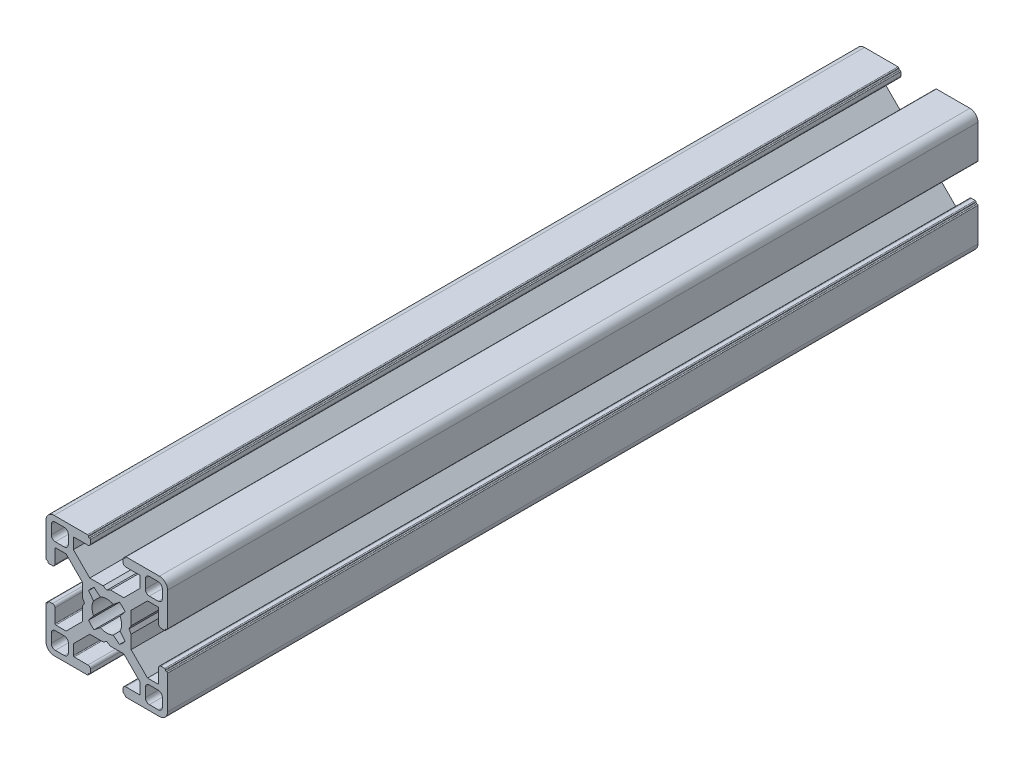
SolidWorks part; units mm, degrees
ref_plane "Płaszczyzna przednia" through (0, 0, 0) normal (0, 0, 1) x (1, 0, 0)
ref_plane "Płaszczyzna górna" through (0, 0, 0) normal (0, 1, 0) x (1, 0, 0)
ref_plane "Płaszczyzna prawa" through (0, 0, 0) normal (1, 0, 0) x (0, 0, -1)
sketch "Szkic1" plane through (0, 0, 0) normal (0, 0, 1) x (1, 0, 0)
  line L0 (109.26, 48.76) -> (107.06, 48.76)
  line L1 (106.06, 47.76) -> (106.06, 45.56)
  line L2 (107.06, 44.56) -> (109.26, 44.56)
  line L3 (110.26, 45.56) -> (110.26, 47.76)
  line L4 (94.9599, 38.3406) -> (93.4241, 39.5784)
  line L5 (92.0547, 38.2147) -> (93.2794, 36.6601)
  line L6 (93.2794, 33.4599) -> (92.0547, 31.9053)
  line L7 (93.4241, 30.5416) -> (94.9599, 31.7794)
  line L8 (98.1601, 31.7794) -> (99.6959, 30.5416)
  line L9 (101.0653, 31.9053) -> (99.8406, 33.4599)
  line L10 (99.8406, 36.6601) -> (101.0653, 38.2147)
  line L11 (99.6959, 39.5784) -> (98.1601, 38.3406)
  line L12 (83.86, 21.36) -> (86.06, 21.36)
  line L13 (87.06, 22.36) -> (87.06, 24.56)
  line L14 (86.06, 25.56) -> (83.86, 25.56)
  line L15 (82.86, 24.56) -> (82.86, 22.36)
  line L16 (110.26, 22.36) -> (110.26, 24.56)
  line L17 (109.26, 25.56) -> (107.06, 25.56)
  line L18 (106.06, 24.56) -> (106.06, 22.36)
  line L19 (86.06, 48.76) -> (83.86, 48.76)
  line L20 (82.86, 47.76) -> (82.86, 45.56)
  line L21 (83.86, 44.56) -> (86.06, 44.56)
  line L22 (87.06, 45.56) -> (87.06, 47.76)
  line L23 (107.06, 21.36) -> (109.26, 21.36)
  line L24 (96.56, 29.5751) -> (97.46, 29.06)
  line L25 (97.46, 29.06) -> (100.7645, 29.06)
  line L26 (100.7645, 29.06) -> (104.81, 25.01)
  line L27 (104.81, 25.01) -> (104.81, 22.46)
  line L28 (104.61, 22.26) -> (101.21, 22.26)
  line L29 (100.61, 21.66) -> (100.61, 20.76)
  line L30 (100.81, 20.56) -> (100.91, 20.56)
  line L31 (101.11, 20.36) -> (101.11, 20.26)
  line L32 (101.31, 20.06) -> (109.56, 20.06)
  line L33 (111.56, 22.06) -> (111.56, 30.31)
  line L34 (111.36, 30.51) -> (111.26, 30.51)
  line L35 (111.06, 30.71) -> (111.06, 30.81)
  line L36 (110.86, 31.01) -> (109.96, 31.01)
  line L37 (109.36, 30.41) -> (109.36, 27.01)
  line L38 (109.16, 26.81) -> (106.61, 26.81)
  line L39 (106.61, 26.81) -> (102.5645, 30.8555)
  line L40 (102.5645, 30.8555) -> (102.5645, 34.16)
  line L41 (102.5645, 34.16) -> (102.0449, 35.06)
  line L42 (102.0449, 35.06) -> (102.5645, 35.96)
  line L43 (102.5645, 35.96) -> (102.5645, 39.2645)
  line L44 (102.5645, 39.2645) -> (106.61, 43.31)
  line L45 (106.61, 43.31) -> (109.16, 43.31)
  line L46 (109.36, 43.11) -> (109.36, 39.71)
  line L47 (109.96, 39.11) -> (110.86, 39.11)
  line L48 (111.06, 39.31) -> (111.06, 39.41)
  line L49 (111.26, 39.61) -> (111.36, 39.61)
  line L50 (111.56, 39.81) -> (111.56, 48.06)
  line L51 (109.56, 50.06) -> (101.31, 50.06)
  line L52 (101.11, 49.86) -> (101.11, 49.76)
  line L53 (100.91, 49.56) -> (100.81, 49.56)
  line L54 (100.61, 49.36) -> (100.61, 48.46)
  line L55 (101.21, 47.86) -> (104.61, 47.86)
  line L56 (104.81, 47.66) -> (104.81, 45.11)
  line L57 (104.81, 45.11) -> (100.7645, 41.06)
  line L58 (100.7645, 41.06) -> (97.46, 41.06)
  line L59 (97.46, 41.06) -> (96.56, 40.5449)
  line L60 (96.56, 40.5449) -> (95.66, 41.06)
  line L61 (95.66, 41.06) -> (92.3555, 41.06)
  line L62 (92.3555, 41.06) -> (88.31, 45.11)
  line L63 (88.31, 45.11) -> (88.31, 47.66)
  line L64 (88.51, 47.86) -> (91.91, 47.86)
  line L65 (92.51, 48.46) -> (92.51, 49.36)
  line L66 (92.31, 49.56) -> (92.21, 49.56)
  line L67 (92.01, 49.76) -> (92.01, 49.86)
  line L68 (91.81, 50.06) -> (83.56, 50.06)
  line L69 (81.56, 48.06) -> (81.56, 39.81)
  line L70 (81.76, 39.61) -> (81.86, 39.61)
  line L71 (82.06, 39.41) -> (82.06, 39.31)
  line L72 (82.26, 39.11) -> (83.16, 39.11)
  line L73 (83.76, 39.71) -> (83.76, 43.11)
  line L74 (83.96, 43.31) -> (86.51, 43.31)
  line L75 (86.51, 43.31) -> (90.5555, 39.2645)
  line L76 (90.5555, 39.2645) -> (90.5555, 35.96)
  line L77 (90.5555, 35.96) -> (91.0751, 35.06)
  line L78 (91.0751, 35.06) -> (90.5555, 34.16)
  line L79 (90.5555, 34.16) -> (90.5555, 30.8555)
  line L80 (90.5555, 30.8555) -> (86.51, 26.81)
  line L81 (86.51, 26.81) -> (83.96, 26.81)
  line L82 (83.76, 27.01) -> (83.76, 30.41)
  line L83 (83.16, 31.01) -> (82.26, 31.01)
  line L84 (82.06, 30.81) -> (82.06, 30.71)
  line L85 (81.86, 30.51) -> (81.76, 30.51)
  line L86 (81.56, 30.31) -> (81.56, 22.06)
  line L87 (83.56, 20.06) -> (91.81, 20.06)
  line L88 (92.01, 20.26) -> (92.01, 20.36)
  line L89 (92.21, 20.56) -> (92.31, 20.56)
  line L90 (92.51, 20.76) -> (92.51, 21.66)
  line L91 (91.91, 22.26) -> (88.51, 22.26)
  line L92 (88.31, 22.46) -> (88.31, 25.01)
  line L93 (88.31, 25.01) -> (92.3555, 29.06)
  line L94 (92.3555, 29.06) -> (95.66, 29.06)
  line L95 (95.66, 29.06) -> (96.56, 29.5751)
  arc A0 (107.06, 48.76) -> (106.06, 47.76) centre (107.06, 47.76) ccw
  arc A1 (106.06, 45.56) -> (107.06, 44.56) centre (107.06, 45.56) ccw
  arc A2 (109.26, 44.56) -> (110.26, 45.56) centre (109.26, 45.56) ccw
  arc A3 (110.26, 47.76) -> (109.26, 48.76) centre (109.26, 47.76) ccw
  arc A4 (93.4241, 39.5784) -> (92.0547, 38.2147) centre (96.56, 35.06) ccw
  arc A5 (93.2794, 36.6601) -> (93.2794, 33.4599) centre (96.56, 35.06) ccw
  arc A6 (92.0547, 31.9053) -> (93.4241, 30.5416) centre (96.56, 35.06) ccw
  arc A7 (94.9599, 31.7794) -> (98.1601, 31.7794) centre (96.56, 35.06) ccw
  arc A8 (99.6959, 30.5416) -> (101.0653, 31.9053) centre (96.56, 35.06) ccw
  arc A9 (99.8406, 33.4599) -> (99.8406, 36.6601) centre (96.56, 35.06) ccw
  arc A10 (101.0653, 38.2147) -> (99.6959, 39.5784) centre (96.56, 35.06) ccw
  arc A11 (98.1601, 38.3406) -> (94.9599, 38.3406) centre (96.56, 35.06) ccw
  arc A12 (86.06, 21.36) -> (87.06, 22.36) centre (86.06, 22.36) ccw
  arc A13 (87.06, 24.56) -> (86.06, 25.56) centre (86.06, 24.56) ccw
  arc A14 (83.86, 25.56) -> (82.86, 24.56) centre (83.86, 24.56) ccw
  arc A15 (82.86, 22.36) -> (83.86, 21.36) centre (83.86, 22.36) ccw
  arc A16 (109.26, 21.36) -> (110.26, 22.36) centre (109.26, 22.36) ccw
  arc A17 (110.26, 24.56) -> (109.26, 25.56) centre (109.26, 24.56) ccw
  arc A18 (107.06, 25.56) -> (106.06, 24.56) centre (107.06, 24.56) ccw
  arc A19 (106.06, 22.36) -> (107.06, 21.36) centre (107.06, 22.36) ccw
  arc A20 (83.86, 48.76) -> (82.86, 47.76) centre (83.86, 47.76) ccw
  arc A21 (82.86, 45.56) -> (83.86, 44.56) centre (83.86, 45.56) ccw
  arc A22 (86.06, 44.56) -> (87.06, 45.56) centre (86.06, 45.56) ccw
  arc A23 (87.06, 47.76) -> (86.06, 48.76) centre (86.06, 47.76) ccw
  arc A24 (104.61, 22.26) -> (104.81, 22.46) centre (104.61, 22.46) ccw
  arc A25 (101.21, 22.26) -> (100.61, 21.66) centre (101.21, 21.66) ccw
  arc A26 (100.61, 20.76) -> (100.81, 20.56) centre (100.81, 20.76) ccw
  arc A27 (101.11, 20.36) -> (100.91, 20.56) centre (100.91, 20.36) ccw
  arc A28 (101.11, 20.26) -> (101.31, 20.06) centre (101.31, 20.26) ccw
  arc A29 (109.56, 20.06) -> (111.56, 22.06) centre (109.56, 22.06) ccw
  arc A30 (111.56, 30.31) -> (111.36, 30.51) centre (111.36, 30.31) ccw
  arc A31 (111.06, 30.71) -> (111.26, 30.51) centre (111.26, 30.71) ccw
  arc A32 (111.06, 30.81) -> (110.86, 31.01) centre (110.86, 30.81) ccw
  arc A33 (109.96, 31.01) -> (109.36, 30.41) centre (109.96, 30.41) ccw
  arc A34 (109.16, 26.81) -> (109.36, 27.01) centre (109.16, 27.01) ccw
  arc A35 (109.36, 43.11) -> (109.16, 43.31) centre (109.16, 43.11) ccw
  arc A36 (109.36, 39.71) -> (109.96, 39.11) centre (109.96, 39.71) ccw
  arc A37 (110.86, 39.11) -> (111.06, 39.31) centre (110.86, 39.31) ccw
  arc A38 (111.26, 39.61) -> (111.06, 39.41) centre (111.26, 39.41) ccw
  arc A39 (111.36, 39.61) -> (111.56, 39.81) centre (111.36, 39.81) ccw
  arc A40 (111.56, 48.06) -> (109.56, 50.06) centre (109.56, 48.06) ccw
  arc A41 (101.31, 50.06) -> (101.11, 49.86) centre (101.31, 49.86) ccw
  arc A42 (100.91, 49.56) -> (101.11, 49.76) centre (100.91, 49.76) ccw
  arc A43 (100.81, 49.56) -> (100.61, 49.36) centre (100.81, 49.36) ccw
  arc A44 (100.61, 48.46) -> (101.21, 47.86) centre (101.21, 48.46) ccw
  arc A45 (104.81, 47.66) -> (104.61, 47.86) centre (104.61, 47.66) ccw
  arc A46 (88.51, 47.86) -> (88.31, 47.66) centre (88.51, 47.66) ccw
  arc A47 (91.91, 47.86) -> (92.51, 48.46) centre (91.91, 48.46) ccw
  arc A48 (92.51, 49.36) -> (92.31, 49.56) centre (92.31, 49.36) ccw
  arc A49 (92.01, 49.76) -> (92.21, 49.56) centre (92.21, 49.76) ccw
  arc A50 (92.01, 49.86) -> (91.81, 50.06) centre (91.81, 49.86) ccw
  arc A51 (83.56, 50.06) -> (81.56, 48.06) centre (83.56, 48.06) ccw
  arc A52 (81.56, 39.81) -> (81.76, 39.61) centre (81.76, 39.81) ccw
  arc A53 (82.06, 39.41) -> (81.86, 39.61) centre (81.86, 39.41) ccw
  arc A54 (82.06, 39.31) -> (82.26, 39.11) centre (82.26, 39.31) ccw
  arc A55 (83.16, 39.11) -> (83.76, 39.71) centre (83.16, 39.71) ccw
  arc A56 (83.96, 43.31) -> (83.76, 43.11) centre (83.96, 43.11) ccw
  arc A57 (83.76, 27.01) -> (83.96, 26.81) centre (83.96, 27.01) ccw
  arc A58 (83.76, 30.41) -> (83.16, 31.01) centre (83.16, 30.41) ccw
  arc A59 (82.26, 31.01) -> (82.06, 30.81) centre (82.26, 30.81) ccw
  arc A60 (81.86, 30.51) -> (82.06, 30.71) centre (81.86, 30.71) ccw
  arc A61 (81.76, 30.51) -> (81.56, 30.31) centre (81.76, 30.31) ccw
  arc A62 (81.56, 22.06) -> (83.56, 20.06) centre (83.56, 22.06) ccw
  arc A63 (91.81, 20.06) -> (92.01, 20.26) centre (91.81, 20.26) ccw
  arc A64 (92.21, 20.56) -> (92.01, 20.36) centre (92.21, 20.36) ccw
  arc A65 (92.31, 20.56) -> (92.51, 20.76) centre (92.31, 20.76) ccw
  arc A66 (92.51, 21.66) -> (91.91, 22.26) centre (91.91, 21.66) ccw
  arc A67 (88.31, 22.46) -> (88.51, 22.26) centre (88.51, 22.46) ccw
  dimension "D1" = 3.65
  dimension "D2" = 30
  dimension "D3" = 30
  dimension "D4" = 8.1
extrude "Dodanie-wyciągnięcie1" add sketch "Szkic1" along normal blind 200
